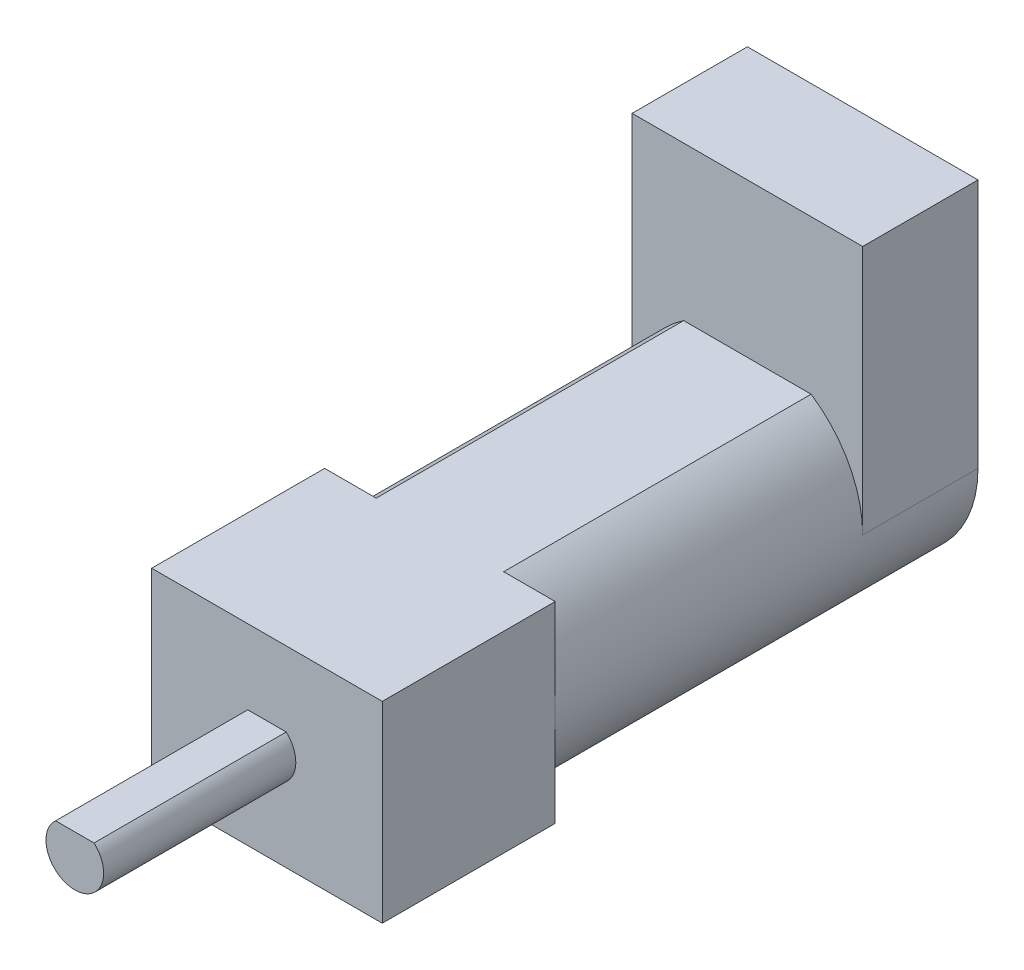
SolidWorks part; units mm, degrees
ref_plane "Plan de face" through (0, 0, 0) normal (0, 0, 1) x (1, 0, 0)
ref_plane "Plan de dessus" through (0, 0, 0) normal (0, 1, 0) x (1, 0, 0)
ref_plane "Plan de droite" through (0, 0, 0) normal (1, 0, 0) x (0, 0, -1)
sketch "Esquisse1" plane through (0, 0, 0) normal (0, 0, 1) x (1, 0, 0)
  line L1 (-6, -5) -> (6, -5)
  line L2 (-6, -5) -> (-6, 5)
  line L3 (-6, 5) -> (6, 5)
  line L4 (6, -5) -> (6, 5)
  line L5 (-6, -5) -> (6, 5) construction
  line L6 (-6, 5) -> (6, -5) construction
  point P0 (0, 0)
  dimension "D1" = 12
  dimension "D2" = 10
extrude "Boss.-Extru.1" add sketch "Esquisse1" along normal blind 9
sketch "Esquisse2" plane through (0, 0, 9) normal (0, 0, 1) x (1, 0, 0)
  line L0 (-1, 1.118) -> (1, 1.118)
  arc A0 (-1, 1.118) -> (1, 1.118) centre (0, 0) ccw
  dimension "D1" = 1.5
  dimension "D2" = 2
extrude "Boss.-Extru.2" add sketch "Esquisse2" along normal blind 10
sketch "Esquisse3" plane through (0, 0, 0) normal (0, 0, -1) x (-1, 0, 0)
  line L0 (-3.3166, 5) -> (3.3166, 5)
  line L1 (-6, 5) -> (6, 5) construction
  line L2 (-3.3166, -5) -> (3.3166, -5)
  line L3 (6, -5) -> (-6, -5) construction
  line L4 (-6, -5) -> (-6, 5) construction
  arc A0 (3.3166, -5) -> (3.3166, 5) centre (0, 0) ccw
  arc A1 (-3.3166, 5) -> (-3.3166, -5) centre (0, 0) ccw
extrude "Boss.-Extru.3" add sketch "Esquisse3" along normal blind 16 contours A1 L2 A0 L0
sketch "Esquisse4" plane through (0, 0, -16) normal (0, 0, -1) x (-1, 0, 0)
  line L0 (-3.3166, -5) -> (3.3166, -5)
  line L2 (-6, 0) -> (-6, 13)
  line L3 (6, 0) -> (6, 13)
  line L4 (-6, 13) -> (6, 13)
  arc A0 (3.3166, -5) -> (6, 0) centre (0, 0) ccw
  arc A1 (-6, 0) -> (-3.3166, -5) centre (0, 0) ccw
  dimension "D1" = 18
extrude "Boss.-Extru.4" add sketch "Esquisse4" along normal blind 6
